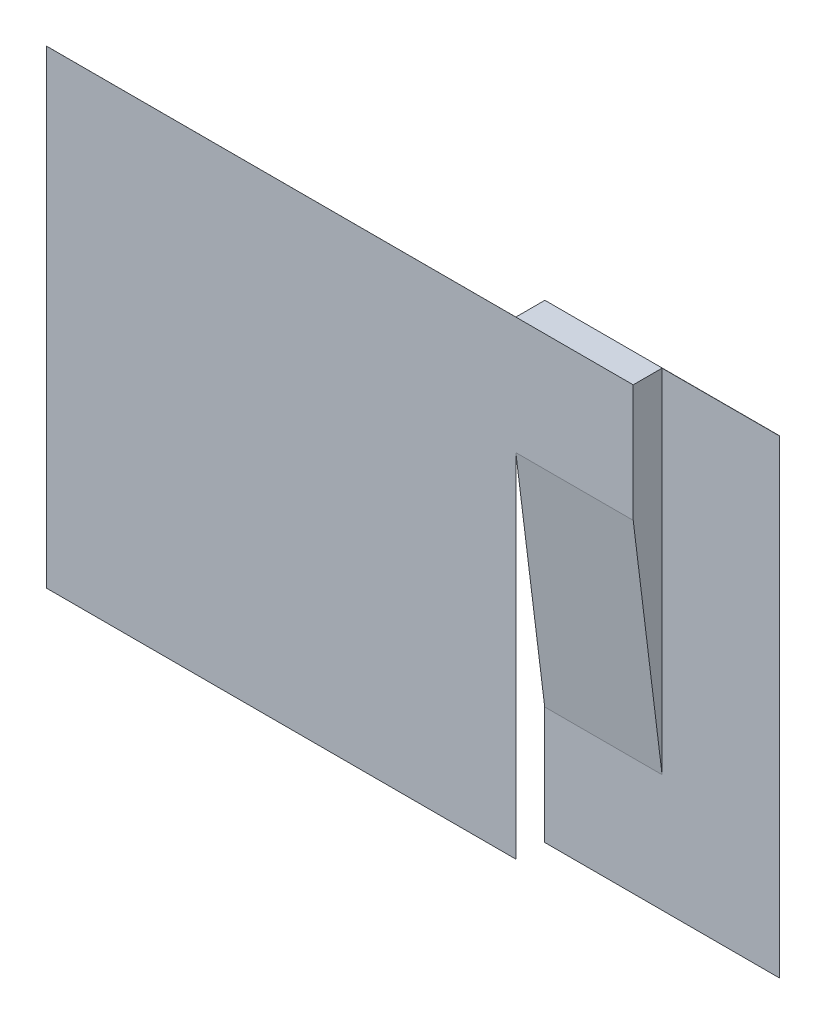
SolidWorks part; units mm, degrees
ref_plane "Front Plane" through (0, 0, 0) normal (0, 0, 1) x (1, 0, 0)
ref_plane "Top Plane" through (0, 0, 0) normal (0, 1, 0) x (1, 0, 0)
ref_plane "Right Plane" through (0, 0, 0) normal (1, 0, 0) x (0, 0, -1)
ref_plane "Plane1" through (0, 0, -425.6093) normal (0, 0, -1) x (-1, 0, 0)
sketch "Sketch1" plane through (0, 0, -425.6093) normal (0, 0, -1) x (-1, 0, 0)
  line L0 (-915, -1901.8205) -> (305, -1901.8205)
  line L1 (305, -1901.8205) -> (305, 538.1795)
  line L2 (305, 538.1795) -> (-915, 538.1795)
  line L3 (-915, 538.1795) -> (-915, -1901.8205)
extrude "Boss-Extrude1" add sketch "Sketch1" against normal blind 1
ref_plane "Plane2" through (0, 538.1795, 0) normal (0, 1, 0) x (1, 0, 0)
sketch "Sketch2" plane through (0, 538.1795, 0) normal (0, 1, 0) x (1, 0, 0)
  line L0 (-305, 274.6093) -> (305, 274.6093)
  line L1 (305, 274.6093) -> (305, 424.6093)
  line L2 (305, 424.6093) -> (-305, 424.6093)
  line L3 (-305, 424.6093) -> (-305, 274.6093)
extrude "Boss-Extrude2" add sketch "Sketch2" against normal blind 1830
sketch "Sketch3" plane through (-305, 0, 0) normal (-1, 0, 0) x (0, 0, 1)
  line L0 (-274.6093, -1291.8205) -> (-274.7093, -1291.8205)
  line L1 (-274.7093, -1291.8205) -> (-274.7093, 538.1795)
  line L2 (-274.7093, 538.1795) -> (-274.6093, 538.1795)
  line L3 (-274.6093, 538.1795) -> (-274.6093, -1291.8205)
extrude "Boss-Extrude3" add sketch "Sketch3" along normal blind 2440
sketch "Sketch4" plane through (0, -1291.8205, 0) normal (0, -1, 0) x (1, 0, 0)
  line L0 (-2745, -274.6093) -> (-305, -274.6093)
  line L1 (-305, -274.6093) -> (-305, -274.7093)
  line L2 (-305, -274.7093) -> (-2745, -274.7093)
  line L3 (-2745, -274.7093) -> (-2745, -274.6093)
extrude "Boss-Extrude4" add sketch "Sketch4" along normal blind 610
draft "Draft1" type of draft neutral plane draft angle 82.991 faces to draft 1 face at (-61, -1291.8205, -334.6293) neutral plane through (0, 0, -424.6093) neutral plane normal (0, 0, 1) parameters "D1"=82.991
